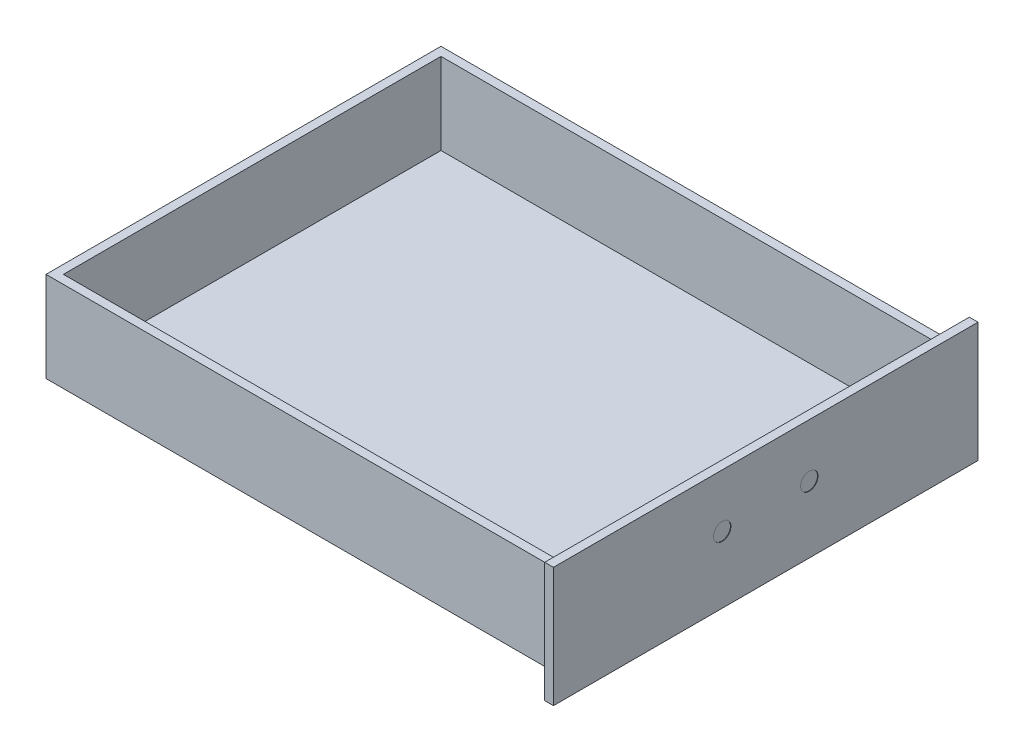
SolidWorks part; units mm, degrees
ref_plane "Front Plane" through (0, 0, 0) normal (0, 0, 1) x (1, 0, 0)
ref_plane "Top Plane" through (0, 0, 0) normal (0, 1, 0) x (1, 0, 0)
ref_plane "Right Plane" through (0, 0, 0) normal (1, 0, 0) x (0, 0, -1)
sketch "Sketch1" plane through (0, 0, 0) normal (1, 0, 0) x (0, 0, -1)
  line L0 (-119.893, 61.1835) -> (367.907, 61.1835)
  line L1 (-102.893, 44.1835) -> (350.907, 44.1835)
  line L2 (-102.893, 44.1835) -> (-102.893, -59.5165)
  line L3 (-102.893, -59.5165) -> (350.907, -59.5165)
  line L4 (350.907, 44.1835) -> (350.907, -59.5165)
  line L5 (367.907, 61.1835) -> (367.907, -76.5165)
  line L6 (-119.893, -76.5165) -> (367.907, -76.5165)
  line L7 (-119.893, 61.1835) -> (-119.893, -76.5165)
  dimension "D1" = 103.7
  dimension "D2" = 453.8
  dimension "D3" = 17
extrude "Boss-Extrude2" add sketch "Sketch1" against normal blind 10
sketch "Sketch4" plane through (0, 0, 0) normal (1, 0, 0) x (0, 0, -1)
  line L0 (-92.893, 34.1835) -> (-92.893, -49.5165)
  line L1 (-102.893, 44.1835) -> (350.907, 44.1835)
  line L2 (-102.893, 44.1835) -> (-102.893, -59.5165)
  line L3 (-102.893, -59.5165) -> (350.907, -59.5165)
  line L4 (350.907, 44.1835) -> (350.907, -59.5165)
  line L5 (-92.893, -49.5165) -> (340.907, -49.5165)
  line L6 (340.907, 34.1835) -> (340.907, -49.5165)
  line L8 (-92.893, 34.1835) -> (-92.893, 44.1835)
  line L9 (340.907, 34.1835) -> (340.907, 44.1835)
  line L11 (-92.893, 34.1835) -> (340.907, 34.1835) construction
  line M9 (-102.893, -59.5165) -> (-102.893, 44.1835)
  line M10 (-102.893, 44.1835) -> (350.907, 44.1835)
  line M11 (350.907, 44.1835) -> (350.907, -59.5165)
  line M12 (350.907, -59.5165) -> (-102.893, -59.5165)
  dimension "D1" = 10
extrude "Boss-Extrude3" add sketch "Sketch4" against normal blind 600 contours L9 L6 L5 L0 L8 M10 M9 M12 M11
sketch "Sketch5" plane through (0, 0, 0) normal (1, 0, 0) x (0, 0, -1)
  line L1 (-92.893, 44.1835) -> (340.907, 44.1835)
  line L2 (-92.893, 44.1835) -> (-92.893, -49.5165)
  line L3 (-92.893, -49.5165) -> (340.907, -49.5165)
  line L4 (340.907, 44.1835) -> (340.907, -49.5165)
extrude "Boss-Extrude4" add sketch "Sketch5" against normal blind 10
sketch "Sketch6" plane through (-600, 0, 0) normal (-1, 0, 0) x (0, 0, 1)
  line L1 (-350.907, 44.1835) -> (102.893, 44.1835)
  line L2 (-350.907, 44.1835) -> (-350.907, -59.5165)
  line L3 (-350.907, -59.5165) -> (102.893, -59.5165)
  line L4 (102.893, 44.1835) -> (102.893, -59.5165)
extrude "Boss-Extrude5" add sketch "Sketch6" against normal blind 10
sketch "Sketch7" plane through (0, 0, 0) normal (1, 0, 0) x (0, 0, -1)
  circle A0 centre (124.007, -11.609) radius 25
  dimension "D1" = 50
extrude "Cut-Extrude2" cut sketch "Sketch7" against normal blind 5
sketch "Sketch8" plane through (0, 0, 0) normal (1, 0, 0) x (0, 0, -1)
  line L1 (77.2669, 25.7552) -> (193.8659, 25.7552)
  line L2 (77.2669, 25.7552) -> (77.2669, -49.6321)
  line L3 (77.2669, -49.6321) -> (193.8659, -49.6321)
  line L4 (193.8659, 25.7552) -> (193.8659, -49.6321)
extrude "Boss-Extrude6" add sketch "Sketch8" against normal blind 9
sketch "Sketch9" plane through (0, 0, 0) normal (1, 0, 0) x (0, 0, -1)
  line L0 (124.007, 61.1835) -> (124.007, -30.3098) construction
  line L1 (367.907, 61.1835) -> (-119.893, 61.1835) construction
  circle A0 centre (74.007, 0) radius 10
  circle A1 centre (174.007, 0) radius 10
  dimension "D1" = 20
  dimension "D2" = 20
  dimension "D3" = 100
  dimension "D4" = 50
extrude "Cut-Extrude4" cut sketch "Sketch9" against normal blind 0.5
